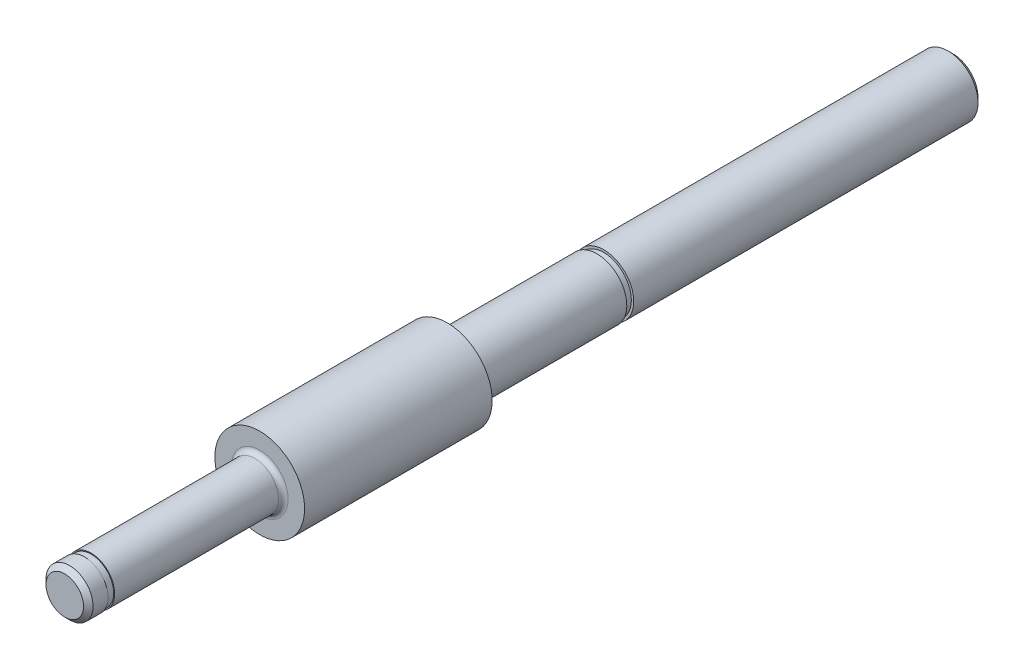
SolidWorks part; units mm, degrees
material "ABS"
ref_plane "Front Plane" through (0, 0, 0) normal (0, 0, 1) x (1, 0, 0)
ref_plane "Top Plane" through (0, 0, 0) normal (0, 1, 0) x (1, 0, 0)
ref_plane "Right Plane" through (0, 0, 0) normal (1, 0, 0) x (0, 0, -1)
sketch "Sketch1" plane through (0, 0, 0) normal (1, 0, 0) x (0, 0, -1)
  line L0 (0, 0) -> (-12.7, 0) construction
  line L1 (-71.7665, 0) -> (-71.7665, 1.992)
  line L2 (-71.7665, 1.992) -> (-71.2585, 2.5)
  line L3 (-71.2585, 2.5) -> (-69.6687, 2.5)
  line L14 (-31.1579, 3.175) -> (-15.2819, 3.175)
  line L15 (22.5082, 3.175) -> (22.5082, 0)
  line L16 (-71.7665, 0) -> (22.5082, 0)
  line L18 (-31.1579, 7.9375) -> (-31.1579, -7.9375) construction
  line L23 (-51.0687, -4.9215) -> (-51.0687, 3.9349) construction
  line L24 (-51.0687, 2.5) -> (-51.0687, 4.7625)
  line L25 (-68.9687, 2.5) -> (-51.0687, 2.5)
  line L26 (-69.6687, 2.5) -> (-69.6687, 2.4)
  line L27 (-68.9687, 2.5) -> (-68.9687, 2.4)
  line L28 (-69.6687, 2.4) -> (-68.9687, 2.4)
  line L29 (-51.0687, 4.7625) -> (-31.1579, 4.7625)
  line L31 (-31.1579, 4.7625) -> (-31.1579, 3.175)
  line L40 (-14.5453, 3.175) -> (22.5082, 3.175)
  line L41 (-15.2819, 3.175) -> (-15.2819, 2.921)
  line L42 (-14.5453, 3.175) -> (-14.5453, 2.921)
  line L43 (-15.2819, 2.921) -> (-14.5453, 2.921)
  point P1 (-14.5453, 3.175)
  dimension "D1" = 5
  dimension "D2" = 0.7
  dimension "D3" = 9.525
  dimension "D4" = 0.7366
  dimension "D5" = 0.1
  dimension "D6" = 0.508
  dimension "D7" = 45
  dimension "D8" = 6.35
  dimension "D9" = 0.254
revolve "Revolve1" add sketch "Sketch1" angle 360 about L0
chamfer "Chamfer1" distance 0.508 angle 45 1 edges at (0, 3.175, -22.5082)
fillet "Fillet1" radius 0.508 2 edges at (0, 3.175, 31.1579) (0, 2.5, 51.0687)
